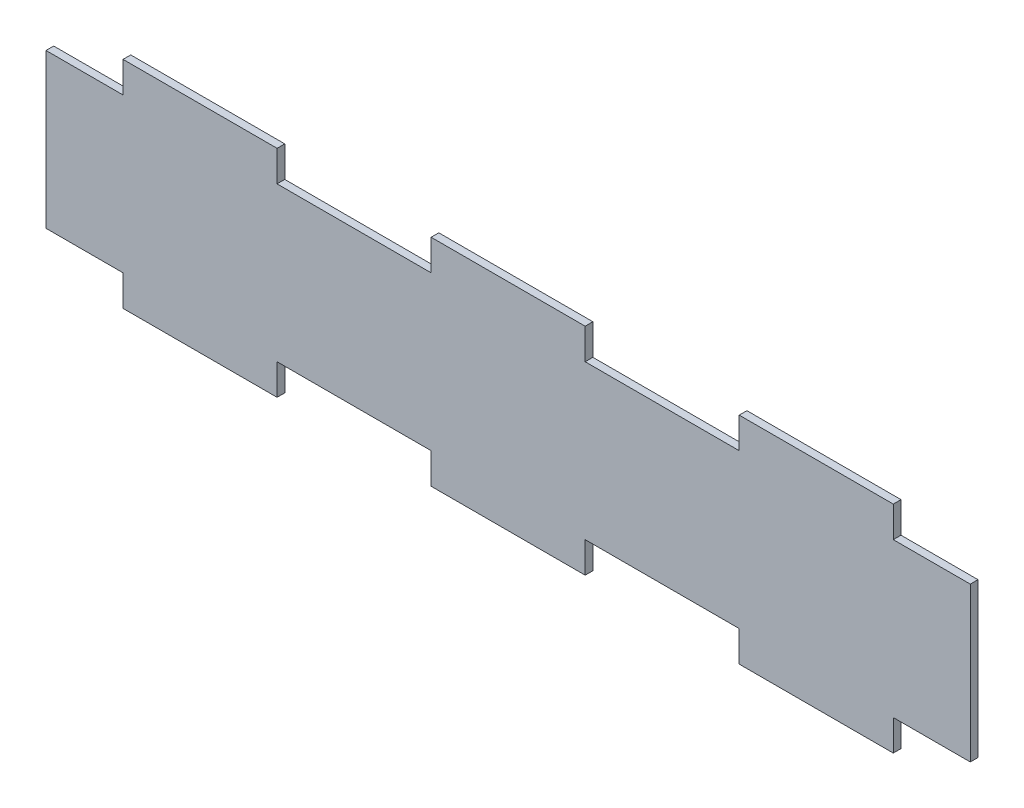
SolidWorks part; units mm, degrees
ref_plane "Front Plane" through (0, 0, 0) normal (0, 0, 1) x (1, 0, 0)
ref_plane "Top Plane" through (0, 0, 0) normal (0, 1, 0) x (1, 0, 0)
ref_plane "Right Plane" through (0, 0, 0) normal (1, 0, 0) x (0, 0, -1)
sketch "Sketch1" plane through (0, 0, 0) normal (0, 0, 1) x (1, 0, 0)
  line L0 (550, 100) -> (600, 100)
  line L1 (600, 100) -> (600, 120)
  line L2 (600, 120) -> (700, 120)
  line L3 (550, 100) -> (550, 0)
  line L4 (700, 120) -> (700, 100)
  line L5 (700, 100) -> (800, 100)
  line L6 (800, 100) -> (800, 120)
  line L7 (800, 120) -> (900, 120)
  line L8 (900, 120) -> (900, 100)
  line L9 (900, 100) -> (1000, 100)
  line L10 (1000, 100) -> (1000, 120)
  line L11 (1000, 120) -> (1100, 120)
  line L12 (1100, 120) -> (1100, 100)
  line L13 (1100, 100) -> (1150, 100)
  line L14 (1150, 100) -> (1150, 0)
  line L15 (1150, 0) -> (1100, 0)
  line L16 (1100, 0) -> (1100, -20)
  line L17 (1100, -20) -> (1000, -20)
  line L18 (1000, -20) -> (1000, 0)
  line L19 (1000, 0) -> (900, 0)
  line L20 (900, 0) -> (900, -20)
  line L21 (900, -20) -> (800, -20)
  line L22 (800, -20) -> (800, 0)
  line L23 (800, 0) -> (700, 0)
  line L24 (700, 0) -> (700, -20)
  line L25 (700, -20) -> (600, -20)
  line L26 (600, -20) -> (600, 0)
  line L27 (600, 0) -> (550, 0)
  dimension "D1" = 100
  dimension "D2" = 100
  dimension "D3" = 20
  dimension "D4" = 50
  dimension "D5" = 100
  dimension "D6" = 100
  dimension "D7" = 100
  dimension "D8" = 50
  dimension "D9" = 20
  dimension "D10" = 100
  dimension "D11" = 50
  dimension "D12" = 20
sketch "Sketch2" plane through (0, 0, 0) normal (0, 0, 1) x (1, 0, 0)
extrude "Boss-Extrude1" add sketch "Sketch1" along normal blind 5
